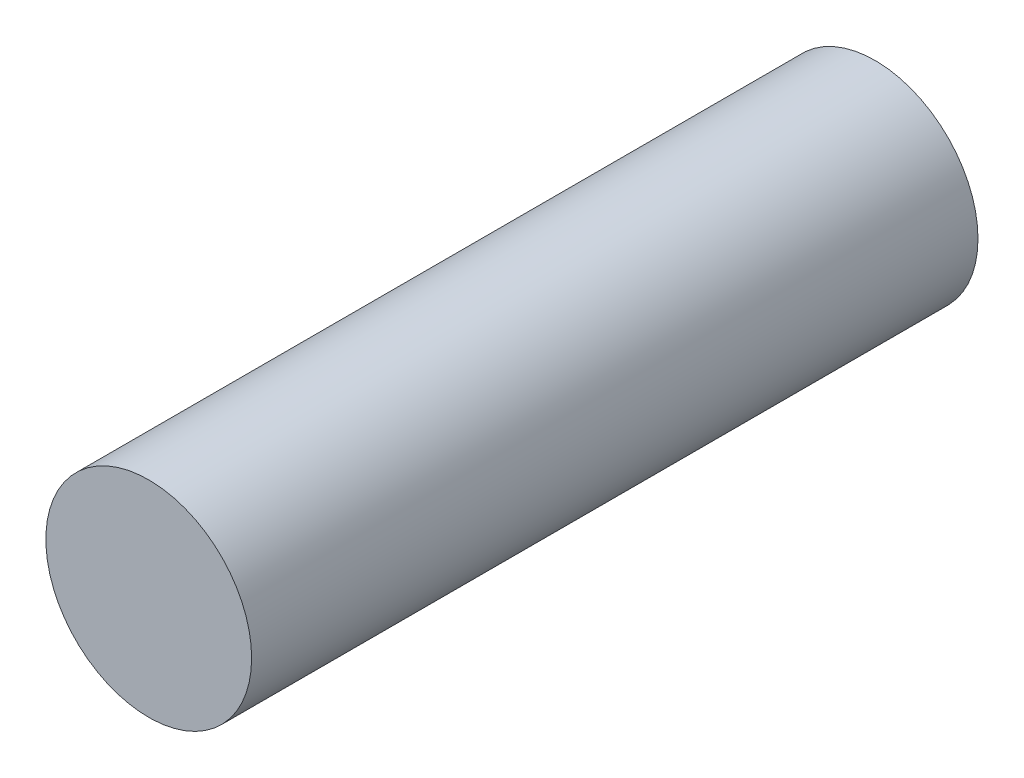
SolidWorks part; units mm, degrees
material "7050-T7651"
ref_plane "Front Plane" through (0, 0, 0) normal (0, 0, 1) x (1, 0, 0)
ref_plane "Top Plane" through (0, 0, 0) normal (0, 1, 0) x (1, 0, 0)
ref_plane "Right Plane" through (0, 0, 0) normal (1, 0, 0) x (0, 0, -1)
sketch "Sketch1" plane through (0, 0, 0) normal (0, 0, 1) x (1, 0, 0)
  circle A0 centre (0, 0) radius 9.25
  dimension "D1" = 18.5
extrude "Boss-Extrude1" add sketch "Sketch1" along normal mid plane 65.3
